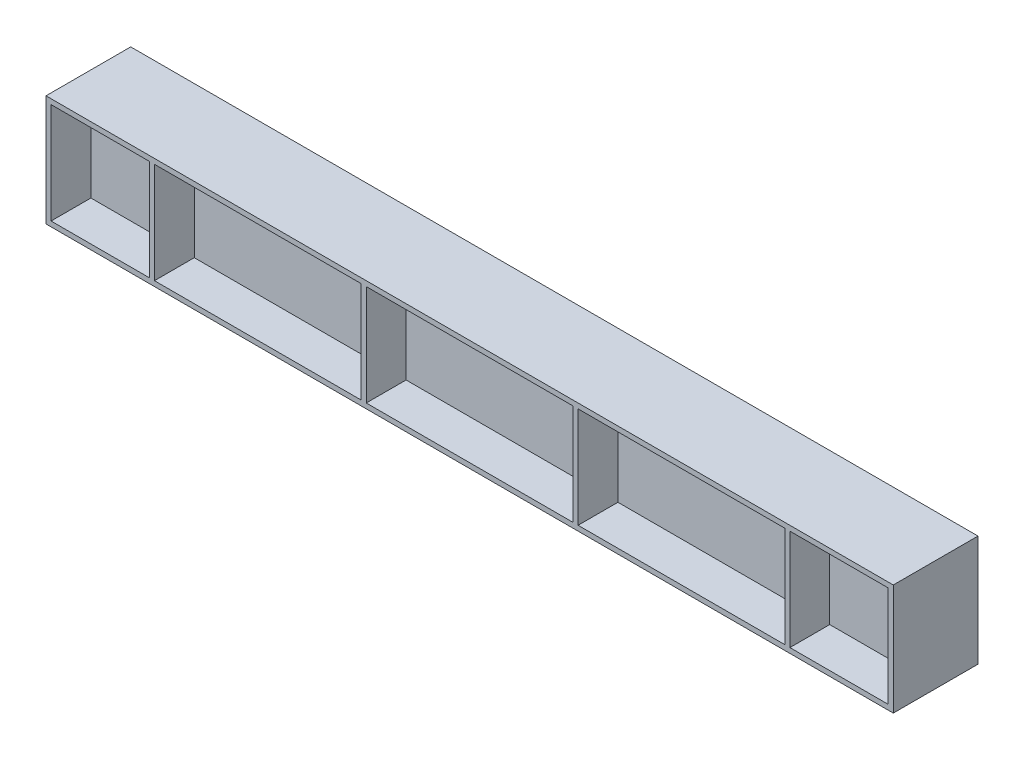
SolidWorks part; units mm, degrees
ref_plane "前视基准面" through (0, 0, 0) normal (0, 0, 1) x (1, 0, 0)
ref_plane "上视基准面" through (0, 0, 0) normal (0, 1, 0) x (1, 0, 0)
ref_plane "右视基准面" through (0, 0, 0) normal (1, 0, 0) x (0, 0, -1)
sketch "草图1" plane through (0, 0, 0) normal (0, 0, 1) x (1, 0, 0)
  line L1 (0, 0) -> (2000, 0)
  line L2 (0, 0) -> (0, 262)
  line L3 (0, 262) -> (2000, 262)
  line L4 (2000, 0) -> (2000, 262)
  dimension "D1" = 2000
  dimension "D2" = 262
extrude "拉伸1" add sketch "草图1" along normal blind 200
sketch "草图5" plane through (0, 0, 200) normal (0, 0, 1) x (1, 0, 0)
  line L0 (2000, 262) -> (0, 262) construction
  line L1 (12, 250) -> (244, 250)
  line L2 (12, 250) -> (12, 12)
  line L3 (12, 12) -> (244, 12)
  line L4 (244, 250) -> (244, 12)
  line L5 (0, 0) -> (2000, 0) construction
  line L6 (0, 262) -> (0, 0) construction
  line L8 (256, 250) -> (744, 250)
  line L9 (256, 250) -> (256, 12)
  line L10 (256, 12) -> (744, 12)
  line L11 (744, 250) -> (744, 12)
  line L12 (756, 250) -> (1244, 250)
  line L13 (756, 250) -> (756, 12)
  line L14 (756, 12) -> (1244, 12)
  line L15 (1244, 250) -> (1244, 12)
  line L16 (1256, 250) -> (1744, 250)
  line L17 (1256, 250) -> (1256, 12)
  line L18 (1256, 12) -> (1744, 12)
  line L19 (1744, 250) -> (1744, 12)
  line L32 (1756, 250) -> (1988, 250)
  line L33 (1756, 250) -> (1756, 12)
  line L34 (1756, 12) -> (1988, 12)
  line L35 (1988, 250) -> (1988, 12)
  dimension "D1" = 12
  dimension "D2" = 12
  dimension "D3" = 12
  dimension "D4" = 232
  dimension "D5" = 12
  dimension "D6" = 488
  dimension "D7" = 488
  dimension "D8" = 12
  dimension "D9" = 488
  dimension "D10" = 12
  dimension "D11" = 12
  dimension "D17" = 232
extrude "拉伸10" cut sketch "草图5" against normal through all
sketch "草图7" plane through (0, 0, 0) normal (0, -1, 0) x (1, 0, 0)
  line L0 (0, 100) -> (3607.9066, 100) construction
  line L1 (0, 200) -> (0, 0) construction
  line L2 (2000, 200) -> (2000, 0) construction
  line L3 (0, 106) -> (2000, 106)
  line L4 (0, 106) -> (0, 94)
  line L5 (0, 94) -> (2000, 94)
  line L6 (2000, 106) -> (2000, 94)
  dimension "D1" = 6
  dimension "D2" = 6
extrude "拉伸13" add sketch "草图7" against normal blind 260
